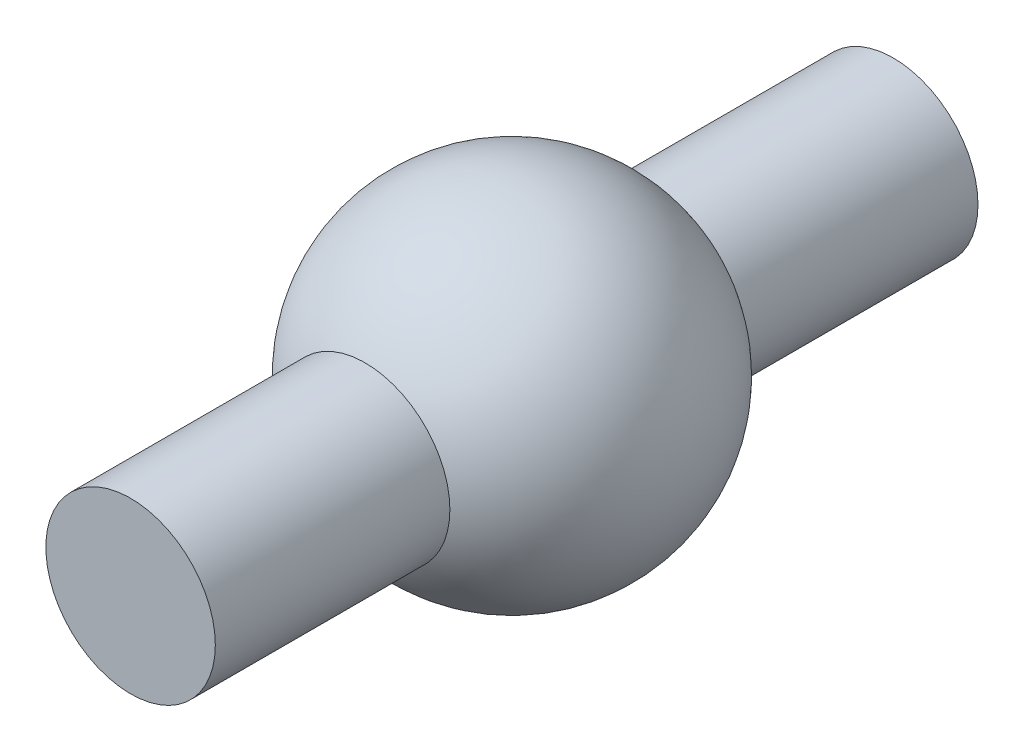
SolidWorks part; units mm, degrees
material "AISI 1020"
ref_plane "Front Plane" through (0, 0, 0) normal (0, 0, 1) x (1, 0, 0)
ref_plane "Top Plane" through (0, 0, 0) normal (0, 1, 0) x (1, 0, 0)
ref_plane "Right Plane" through (0, 0, 0) normal (1, 0, 0) x (0, 0, -1)
sketch "Sketch1" plane through (0, 0, 0) normal (0, 1, 0) x (1, 0, 0)
  line L0 (0, 2.54) -> (0, -2.54)
  arc A0 (0, 2.54) -> (0, -2.54) centre (0, 0) cw
  dimension "D1" = 2.54
revolve "Revolve1" add sketch "Sketch1" angle 360 about L0
sketch "Sketch2" plane through (0, 0, 0) normal (0, 0, 1) x (1, 0, 0)
  circle A0 centre (0, 0) radius 1.27
  dimension "D1" = 2.54
extrude "Boss-Extrude1" add sketch "Sketch2" along normal mid plane 11.43
